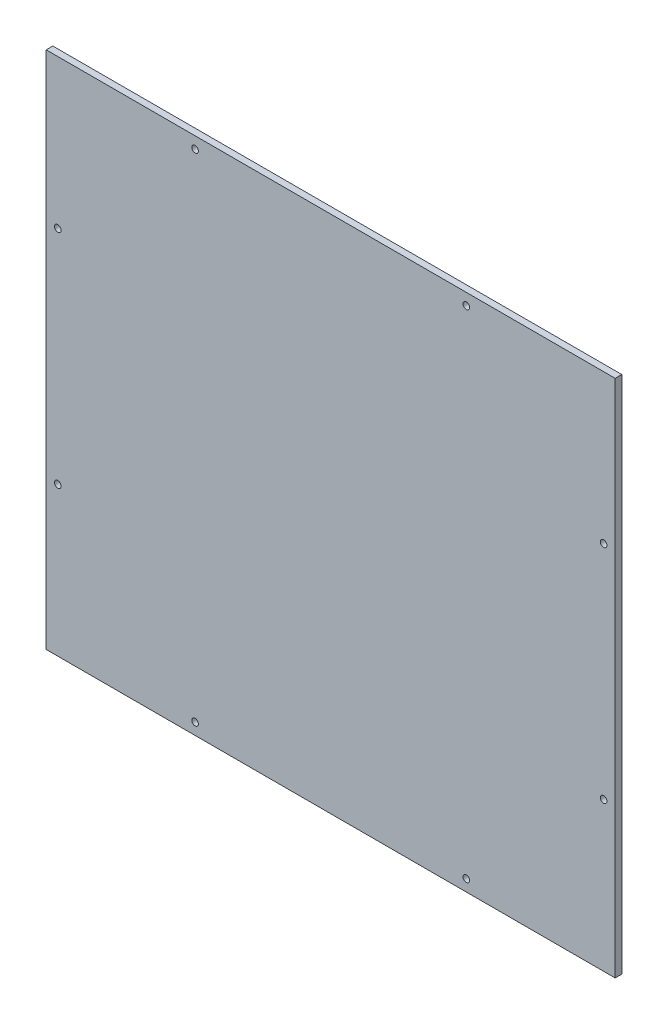
SolidWorks part; units mm, degrees
ref_plane "Piano frontale" through (0, 0, 0) normal (0, 0, 1) x (1, 0, 0)
ref_plane "Piano superiore" through (0, 0, 0) normal (0, 1, 0) x (1, 0, 0)
ref_plane "Piano destro" through (0, 0, 0) normal (1, 0, 0) x (0, 0, -1)
sketch "Schizzo1" plane through (0, 0, 0) normal (0, 0, 1) x (1, 0, 0)
  line L0 (-172, 351.6275) -> (-172, -66.2585) construction
  line L1 (0, 0) -> (-344, 0)
  line L2 (0, 0) -> (0, 314)
  line L3 (0, 314) -> (-344, 314)
  line L4 (-344, 0) -> (-344, 314)
  line L5 (-387.9788, 157) -> (120.8821, 157) construction
  circle A0 centre (-90, 307) radius 2
  circle A1 centre (-7, 224) radius 2
  circle A2 centre (-254, 307) radius 2
  circle A3 centre (-337, 224) radius 2
  circle A4 centre (-254, 7) radius 2
  circle A5 centre (-337, 90) radius 2
  circle A6 centre (-7, 90) radius 2
  circle A7 centre (-90, 7) radius 2
  point P9 (-172, 157)
  dimension "D3" = 4
  dimension "D1" = 344
  dimension "314" = 314
  dimension "D4" = 7
  dimension "D5" = 90
  dimension "D6" = 7
  dimension "D7" = 90
extrude "Estrusione-Estrusione1" add sketch "Schizzo1" along normal blind 4
